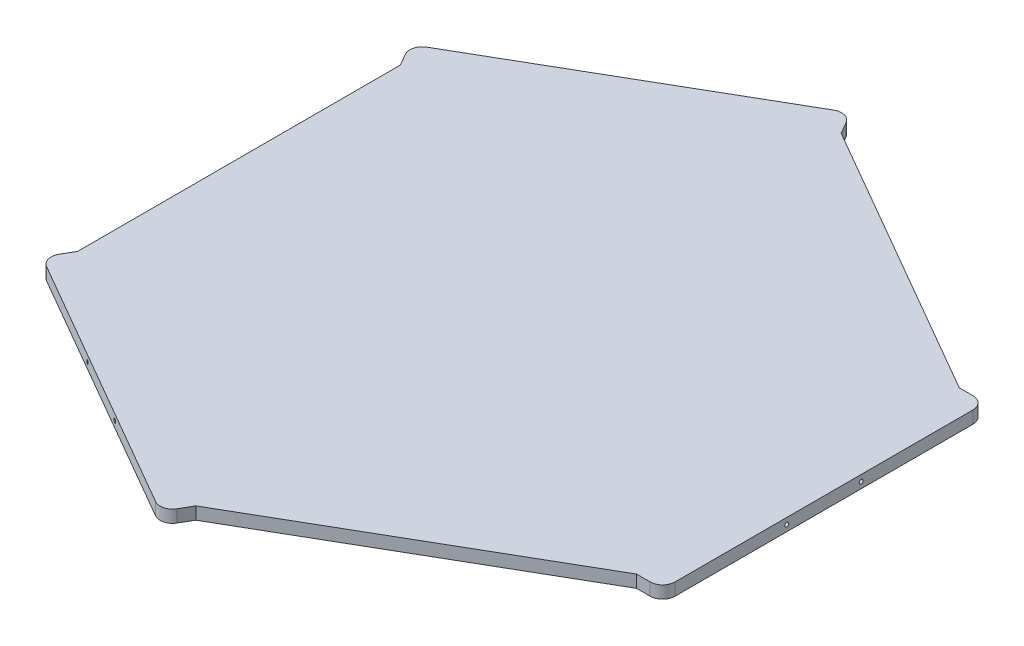
SolidWorks part; units mm, degrees
ref_plane "前视基准面" through (0, 0, 0) normal (0, 0, 1) x (1, 0, 0)
ref_plane "上视基准面" through (0, 0, 0) normal (0, 1, 0) x (1, 0, 0)
ref_plane "右视基准面" through (0, 0, 0) normal (1, 0, 0) x (0, 0, -1)
sketch "草图1" plane through (0, 0, 0) normal (0, 1, 0) x (1, 0, 0)
  line L0 (-112.5833, -65) -> (0, -130)
  line L1 (0, -130) -> (112.5833, -65)
  line L2 (112.5833, -65) -> (112.5833, 65)
  line L3 (112.5833, 65) -> (0, 130)
  line L4 (0, 130) -> (-112.5833, 65)
  line L5 (-112.5833, 65) -> (-112.5833, -65)
  line L6 (-112.5833, -65) -> (0, -130)
  line L7 (-112.5833, -65) -> (-115.3333, -69.7631)
  line L8 (0, -130) -> (-2.75, -134.7631)
  line L9 (-113.5032, -76.5933) -> (-9.5801, -136.5933)
  line L10 (112.5833, 65) -> (112.5833, -65)
  line L11 (112.5833, 65) -> (118.0833, 65)
  line L12 (112.5833, -65) -> (118.0833, -65)
  line L13 (123.0833, 60) -> (123.0833, -60)
  line L14 (0, 130) -> (-112.5833, 65)
  line L15 (0, 130) -> (-2.75, 134.7631)
  line L16 (-112.5833, 65) -> (-115.3333, 69.7631)
  line L17 (-9.5801, 136.5933) -> (-113.5032, 76.5933)
  circle A0 centre (0, 0) radius 112.5833 construction
  arc A1 (118.0833, -65) -> (123.0833, -60) centre (118.0833, -60) ccw
  arc A2 (123.0833, 60) -> (118.0833, 65) centre (118.0833, 60) ccw
  arc A3 (-9.5801, 136.5933) -> (-2.75, 134.7631) centre (-7.0801, 132.2631) cw
  arc A4 (-115.3333, 69.7631) -> (-113.5032, 76.5933) centre (-111.0032, 72.2631) cw
  arc A5 (-113.5032, -76.5933) -> (-115.3333, -69.7631) centre (-111.0032, -72.2631) cw
  arc A6 (-9.5801, -136.5933) -> (-2.75, -134.7631) centre (-7.0801, -132.2631) ccw
  point P17 (123.0833, -65)
  point P24 (-117.8333, 74.0933)
  point P29 (-5.25, -139.0933)
  dimension "D5" = 5
  dimension "D1" = 130
  dimension "D2" = 10.5
  dimension "D3" = 10.5
  dimension "D4" = 10.5
extrude "凸台-拉伸1" add sketch "草图1" along normal blind 5 contours L4 L5 L0 L1 L2 L3 | L7 L9 L8 L0 | L13 L11 L2 L12 | L15 L17 L16 L4
sketch "草图11" plane through (-61.5417, 0, 106.5933) normal (-0.5, 0, 0.866) x (0.866, 0, 0.5)
  line L0 (0, 5) -> (0, 0) construction
  line L1 (-60, 5) -> (60, 5) construction
  line L2 (-60, 2.5) -> (60, 2.5) construction
  line L3 (-60, 5) -> (-60, 0) construction
  line L4 (60, 5) -> (60, 0) construction
  circle A0 centre (-15, 2.5) radius 1
  circle A1 centre (15, 2.5) radius 1
  dimension "D1" = 15
  dimension "D2" = 15
sketch "草图12" plane through (-61.5417, 0, -106.5933) normal (-0.5, 0, -0.866) x (-0.866, 0, 0.5)
  line L0 (0, 5) -> (0, 0) construction
  line L1 (-60, 5) -> (60, 5) construction
  line L2 (60, 2.5) -> (-60, 2.5) construction
  line L3 (60, 5) -> (60, 0) construction
  line L4 (-60, 5) -> (-60, 0) construction
  circle A0 centre (-15, 2.5) radius 1
  circle A1 centre (15, 2.5) radius 1
  dimension "D1" = 15
  dimension "D2" = 15
sketch "草图13" plane through (123.0833, 0, 0) normal (1, 0, 0) x (0, 0, -1)
  line L0 (0, 5) -> (0, 0) construction
  line L1 (60, 5) -> (-60, 5) construction
  line L2 (-60, 2.5) -> (60, 2.5) construction
  line L3 (-60, 5) -> (-60, 0) construction
  line L4 (60, 5) -> (60, 0) construction
  circle A0 centre (-15, 2.5) radius 1
  circle A1 centre (15, 2.5) radius 1
  point P11 (-15, 2.5)
  point P13 (15, 2.5)
  dimension "D1" = 15
  dimension "D2" = 15
hole_wizard "M2 螺纹孔1" positions "草图13" profile "草图14" tap size "M2" standard "GB"
sketch "草图14" plane through (123.0833, 2.5, -15) normal (0, 1, 0) x (0, 0, -1)
  line L0 (0, 0) -> (0, 7.2)
  line L1 (0, 7.2) -> (0.8, 6.7193)
  line L2 (0.8, 6.7193) -> (0.8, 0)
  line L5 (0.8, 0) -> (0, 0)
  line L10 (0, 7.2) -> (-0.8, 6.7193) construction
  line L11 (0, -6.35) -> (0, 107.95) construction
  dimension "螺纹孔钻头直径" = 1.6
  dimension "螺纹孔钻头深度" = 7.2
  dimension "导头角度" = 118
cosmetic thread "孔螺蚊线1" parameters "D1"=6, "D2"=2
cosmetic thread "孔螺蚊线2" parameters "D1"=6, "D2"=2
hole_wizard "M2 螺纹孔2" positions "3D草图1" profile "草图15" tap size "M2" standard "GB"
sketch3d "3D草图1"
  point P0 (-48.5513, 2.5, 114.0933)
  point P3 (-74.532, 2.5, 99.0933)
  point P6 (-74.532, 2.5, -99.0933)
  point P9 (-48.5513, 2.5, -114.0933)
sketch "草图15" plane through (-48.5513, 2.5, 114.0933) normal (0, 1, 0) x (0.866, 0, 0.5)
  line L0 (0, 0) -> (0, 7.2)
  line L1 (0, 7.2) -> (0.8, 6.7193)
  line L2 (0.8, 6.7193) -> (0.8, 0)
  line L5 (0.8, 0) -> (0, 0)
  line L10 (0, 7.2) -> (-0.8, 6.7193) construction
  line L11 (0, -6.35) -> (0, 107.95) construction
  dimension "螺纹孔钻头直径" = 1.6
  dimension "螺纹孔钻头深度" = 7.2
  dimension "导头角度" = 118
cosmetic thread "孔螺蚊线3" parameters "D1"=6, "D2"=2
cosmetic thread "孔螺蚊线4" parameters "D1"=6, "D2"=2
cosmetic thread "孔螺蚊线5" parameters "D1"=6, "D2"=2
cosmetic thread "孔螺蚊线6" parameters "D1"=6, "D2"=2
